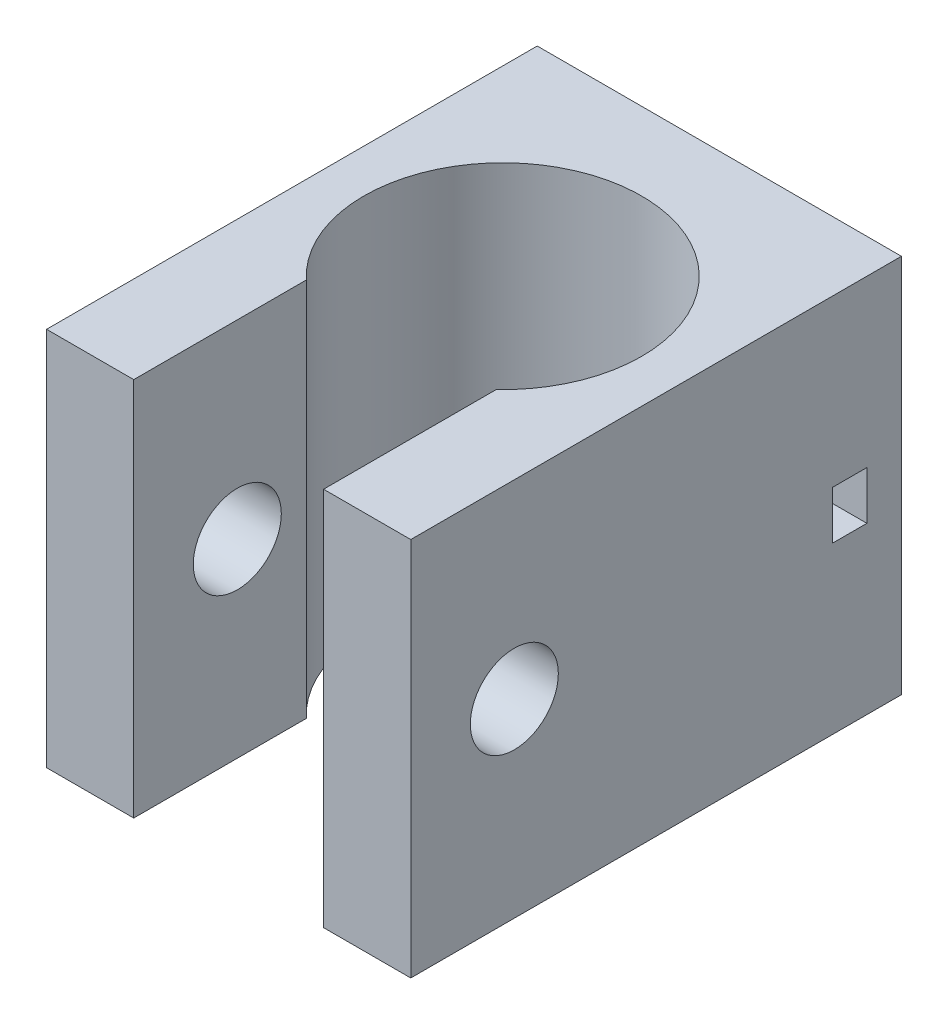
SolidWorks part; units mm, degrees
ref_plane "Front Plane" through (0, 0, 0) normal (0, 0, 1) x (1, 0, 0)
ref_plane "Top Plane" through (0, 0, 0) normal (0, 1, 0) x (1, 0, 0)
ref_plane "Right Plane" through (0, 0, 0) normal (1, 0, 0) x (0, 0, -1)
sketch "Sketch1" plane through (0, 0, 0) normal (0, 1, 0) x (1, 0, 0)
  line L0 (-5.5, -15) -> (-10.55, -15)
  line L1 (-10.55, -15) -> (-10.55, 13.4281)
  line L2 (-10.55, 13.4281) -> (10.55, 13.4281)
  line L3 (10.55, 13.4281) -> (10.55, -15)
  line L4 (10.55, -15) -> (5.5, -15)
  line L5 (5.5, -15) -> (5.5, -5)
  line L6 (-5.5, -15) -> (-5.5, -5)
  line L7 (-44.2539, 0) -> (44.2539, 0) construction
  line L8 (0, -44.7868) -> (0, 44.7868) construction
  arc A0 (-5.5, -5) -> (5.5, -5) centre (0, 0.8781) cw
  dimension "D1" = 8.05
  dimension "D2" = 11
  dimension "D3" = 10
  dimension "D4" = 10
  dimension "D5" = 21.1
  dimension "D6" = 12.55
  dimension "D7" = 15
  dimension "D8" = 10.55
extrude "Boss-Extrude1" add sketch "Sketch1" along normal mid plane 22
sketch "Sketch2" plane through (10.55, 0, 0) normal (1, 0, 0) x (0, 0, -1)
  line L0 (55, 0) -> (-55, 0) construction
  line L1 (-15, 11) -> (-15, -11) construction
  circle A0 centre (-9, 0) radius 2.55
  dimension "D1" = 6
  dimension "D2" = 5.1
extrude "Cut-Extrude1" cut sketch "Sketch2" against normal up to surface (21.1 mm away) up to face at (-10.55, 0, 0.7859)
sketch "Sketch4" plane through (10.55, 0, 0) normal (1, 0, 0) x (0, 0, -1)
  line L1 (9.4281, 1.4) -> (11.4281, 1.4)
  line L2 (9.4281, 1.4) -> (9.4281, -1.4)
  line L3 (9.4281, -1.4) -> (11.4281, -1.4)
  line L4 (11.4281, 1.4) -> (11.4281, -1.4)
  line L5 (-15, 11) -> (13.4281, 11) construction
  line L7 (13.4281, 11) -> (13.4281, -11) construction
  point P6 (10.4281, 1.4)
  dimension "D1" = 2
  dimension "D2" = 2.8
  dimension "D3" = 9.6
  dimension "D4" = 2
extrude "Cut-Extrude3" cut sketch "Sketch4" against normal up to surface (21.1 mm away) up to face at (-10.55, 0, 6.45)
sketch "Sketch5" plane through (0, 0, -13.4281) normal (0, 0, -1) x (-1, 0, 0)
  line L0 (10.55, 11) -> (10.55, -11) construction
  line L1 (-2.5, 8.5) -> (2.5, 8.5)
  line L2 (-2.5, 8.5) -> (-2.5, 3.5)
  line L3 (-2.5, 3.5) -> (2.5, 3.5)
  line L4 (2.5, 8.5) -> (2.5, 3.5)
  line L5 (2.5, -3.5) -> (-2.5, -3.5)
  line L6 (2.5, -3.5) -> (2.5, -8.5)
  line L7 (2.5, -8.5) -> (-2.5, -8.5)
  line L8 (-2.5, -3.5) -> (-2.5, -8.5)
  line L10 (-10.55, 11) -> (10.55, 11) construction
  line L11 (-10.55, -11) -> (10.55, -11) construction
  dimension "D1" = 5
  dimension "D2" = 5
  dimension "D3" = 5
  dimension "D4" = 5
  dimension "D5" = 8.05
  dimension "D6" = 8.05
  dimension "D7" = 2.5
  dimension "D8" = 2.5
extrude "Cut-Extrude5" cut sketch "Sketch5" against normal blind 2
equation "\"Width\"=21.1"
equation "\"D5@Sketch1\"=\"Width\""
equation "\"D8@Sketch1\"=\"Width\"/2"
equation "\"D6@Sketch1\"=\"Width\"/2+2"
